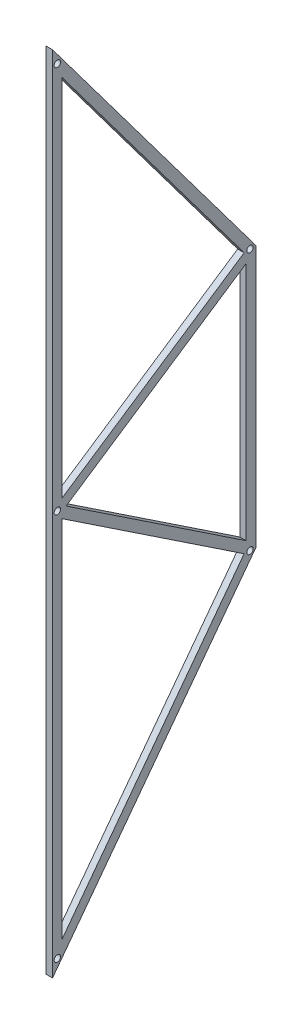
SolidWorks part; units mm, degrees
material "AISI 1020 Steel, Cold Rolled"
ref_plane "Front Plane" through (0, 0, 0) normal (1, 0, 0) x (0, 1, 0)
ref_plane "Top Plane" through (0, 0, 0) normal (0, 0, 1) x (0, 1, 0)
ref_plane "Right Plane" through (0, 0, 0) normal (0, 1, 0) x (-1, 0, 0)
sketch "Sketch4" plane through (0, 0, 0) normal (1, 0, 0) x (0, 1, 0)
  line L0 (-600, 0) -> (600, 0)
  line L2 (0, 0) -> (0, -500) construction
  line L4 (-200, -300) -> (200, -300)
  line L5 (-600, 0) -> (-200, -300)
  line L6 (600, 0) -> (200, -300)
  line L7 (0, 0) -> (-200, -300)
  line L8 (0, 0) -> (200, -300)
  line L9 (-577.5, -7.5) -> (-197.5, -292.5)
  line L10 (-577.5, -7.5) -> (577.5, -7.5)
  line L11 (577.5, -7.5) -> (197.5, -292.5)
  line L12 (-202.5, -307.5) -> (202.5, -307.5)
  line L13 (-622.5, 7.5) -> (-202.5, -307.5)
  line L14 (-622.5, 7.5) -> (622.5, 7.5)
  line L15 (622.5, 7.5) -> (202.5, -307.5)
  line L16 (-197.5, -292.5) -> (197.5, -292.5)
  line L17 (-200, -292.5) -> (200, -292.5) construction
  line L18 (-622.5, 7.5) -> (-204.5, -306) construction
  line L19 (-200, -307.5) -> (200, -307.5) construction
  line L20 (-577.5, -7.5) -> (-195.5, -294) construction
  line L21 (577.5, -7.5) -> (195.5, -294) construction
  line L22 (9.0139, 0) -> (201.8426, -289.2431)
  line L23 (-9.0139, 0) -> (-201.8426, -289.2431)
  line L24 (0, -13.5208) -> (195.9861, -307.5)
  line L25 (0, -13.5208) -> (-195.9861, -307.5)
  line L26 (0, 13.5208) -> (-206.2404, -295.8397) construction
  line L27 (0, 13.5208) -> (206.2404, -295.8397) construction
  line L28 (622.5, 7.5) -> (204.5, -306) construction
  line L29 (0, -13.5208) -> (-193.7596, -304.1603) construction
  line L30 (0, -13.5208) -> (193.7596, -304.1603) construction
  point P3 (4078.1491, 0)
  point P4 (8532.6478, 0)
  point P11 (0, -300)
  dimension "D1" = 1200
  dimension "D2" = 500
  dimension "D3" = 400
  dimension "D4" = 300
  dimension "D5" = 7.5
  dimension "D6" = 7.5
  dimension "D7" = 7.5
  dimension "D8" = 7.5
extrude "Boss-Extrude2" add sketch "Sketch4" along normal blind 10 contours L16 L25 L4 L24 | L0 L22 L10 L11 L16 L8 L6 | L25 L4 L5 L0 L6 L24 L12 L15 L14 L13 | L23 L0 L5 L7 L16 L9 L10 | L10 L23 L9 L16 L7 | L25 L24 L16 L8 L10 L7 | L25 L16 L7 L4 | L4 L25 L12 L24 | L22 L10 L8 L16 L11 | L16 L24 L4 L8 | L0 L23 L10 L7 | L22 L0 L8 L10 | L7 L10 L8
sketch "Sketch6" plane through (10, 0, 0) normal (1, 0, 0) x (0, 1, 0)
  line L0 (0, 0) -> (748.5181, 0) construction
  line L1 (0, 0) -> (-600, 0) construction
  line L2 (0, 0) -> (0, -359.3172) construction
  line L3 (-202.2746, -298.294) -> (202.2746, -298.294) construction
  line L5 (202.2746, -298.294) -> (600, 0) construction
  line L7 (-202.2746, -298.294) -> (-600, 0) construction
  circle A0 centre (0, 0) radius 5
  circle A1 centre (-600, 0) radius 5
  circle A2 centre (-202.2746, -298.294) radius 5
  circle A3 centre (202.2746, -298.294) radius 5
  circle A4 centre (600, 0) radius 5
  dimension "D1" = 10
  dimension "D2" = 10
  dimension "D3" = 10
  dimension "D4" = 10
  dimension "D5" = 10
extrude "Cut-Extrude3" cut sketch "Sketch6" against normal blind 10
